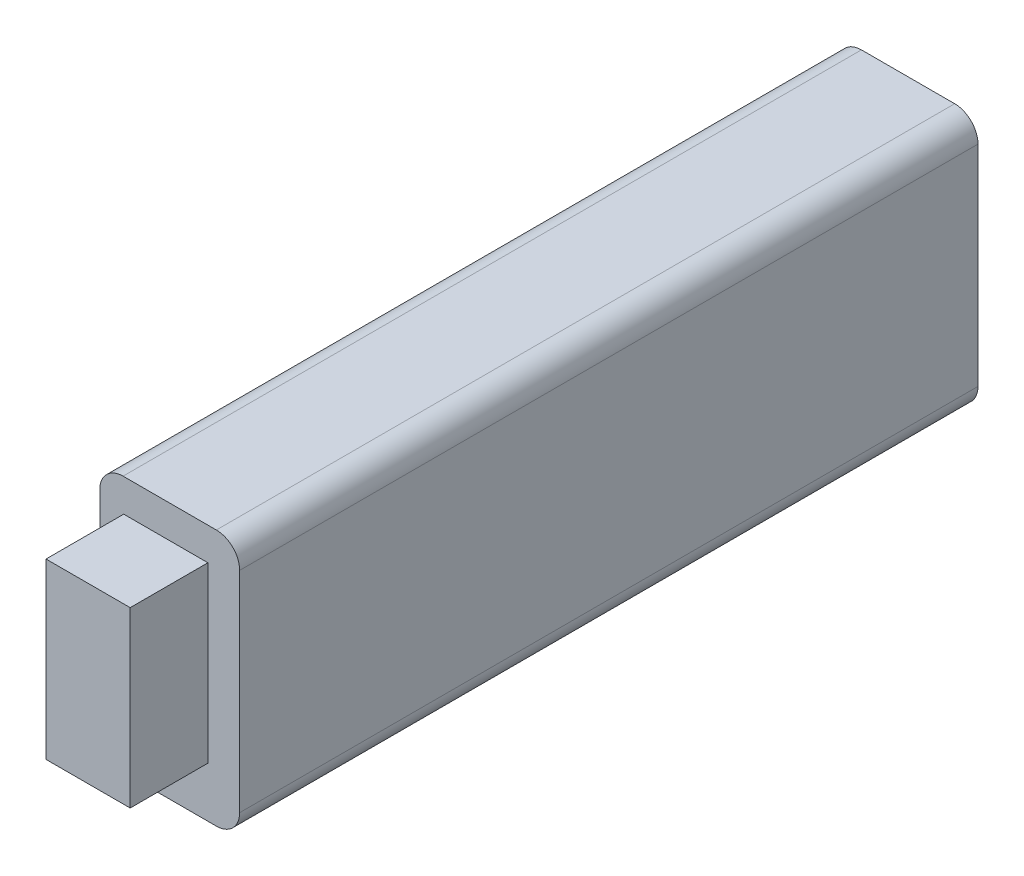
SolidWorks part; units mm, degrees
material "FR-4 (Glass Epoxy PCB)"
ref_plane "Front Plane" through (0, 0, 0) normal (0, 0, 1) x (1, 0, 0)
ref_plane "Top Plane" through (0, 0, 0) normal (0, 1, 0) x (1, 0, 0)
ref_plane "Right Plane" through (0, 0, 0) normal (1, 0, 0) x (0, 0, -1)
sketch "Sketch1" plane through (0, 0, 0) normal (1, 0, 0) x (0, 0, -1)
  line L1 (-47.5, -16.5) -> (47.5, -16.5)
  line L2 (-47.5, -16.5) -> (-47.5, 16.5)
  line L3 (-47.5, 16.5) -> (47.5, 16.5)
  line L4 (47.5, -16.5) -> (47.5, 16.5)
  line L5 (-47.5, -16.5) -> (47.5, 16.5) construction
  line L6 (-47.5, 16.5) -> (47.5, -16.5) construction
  point P0 (0, 0)
  dimension "D1" = 95
  dimension "D2" = 33
extrude "Boss-Extrude1" add sketch "Sketch1" along normal blind 18
sketch "Sketch2" plane through (0, 0, 47.5) normal (0, 0, 1) x (1, 0, 0)
  line L1 (3.0824, 12.3055) -> (13.9143, 12.3055)
  line L2 (3.0824, 12.3055) -> (3.0824, -10.0263)
  line L3 (3.0824, -10.0263) -> (13.9143, -10.0263)
  line L4 (13.9143, 12.3055) -> (13.9143, -10.0263)
extrude "Boss-Extrude2" add sketch "Sketch2" along normal blind 10
fillet "Fillet1" radius 3 4 edges at (0, 16.5, 0) (0, -16.5, 0) (18, 16.5, 0) (18, -16.5, 0)
